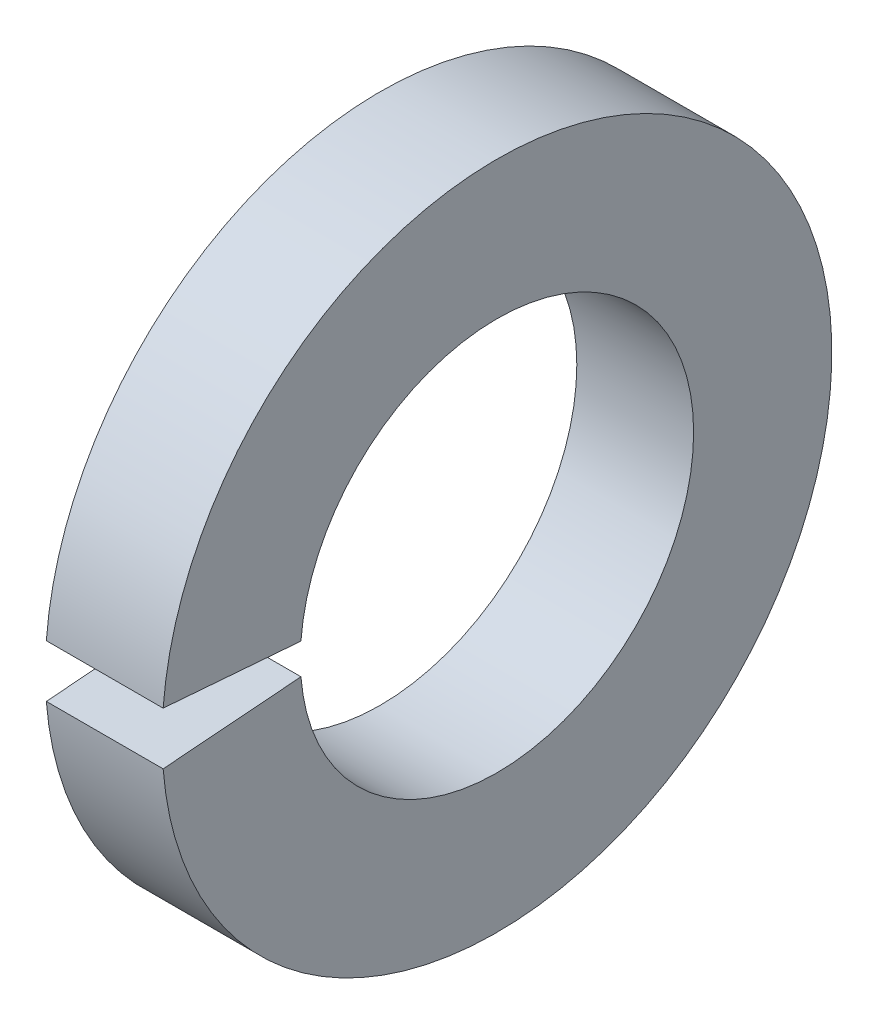
SolidWorks part; units mm, degrees
ref_plane "Plane1" through (0, 0, 0) normal (0, 0, 1) x (1, 0, 0)
ref_plane "Plane2" through (0, 0, 0) normal (0, 1, 0) x (1, 0, 0)
ref_plane "Plane3" through (0, 0, 0) normal (1, 0, 0) x (0, 0, -1)
sketch "Sketch1" plane through (0, 0, 0) normal (0, 0, 1) x (1, 0, 0)
  line L0 (-34.925, 0) -> (9.525, 0) construction
  line L1 (0, 10.1) -> (0, 17.2)
  line L2 (0, 17.2) -> (-6, 17.2)
  line L3 (-6, 17.2) -> (-6, 10.1)
  line L4 (-6, 10.1) -> (0, 10.1)
  dimension "Thickness" = 6
  dimension "Inside_dia" = 20.2
  dimension "Outside_dia" = 34.4
revolve "Base-Revolve" add sketch "Sketch1" angle 360 about L0
sketch "Sketch2" plane through (0, 0, 0) normal (-1, 0, 0) x (0, -1, 0)
  line L0 (0, 0) -> (1.3765, 17.4899)
  line L1 (0, -3.175) -> (0, 12.7) construction
  line L2 (0, 0) -> (-1.3765, 17.4899)
  arc A0 (1.3765, 17.4899) -> (-1.3765, 17.4899) centre (0, 0) ccw
  dimension "Gap_ang" = 9
  dimension "D1" = 17.544
extrude "Gap" cut sketch "Sketch2" along normal through all
equation "\"D1@Sketch2\" = \"Outside_dia@Sketch1\" * 0.51"
